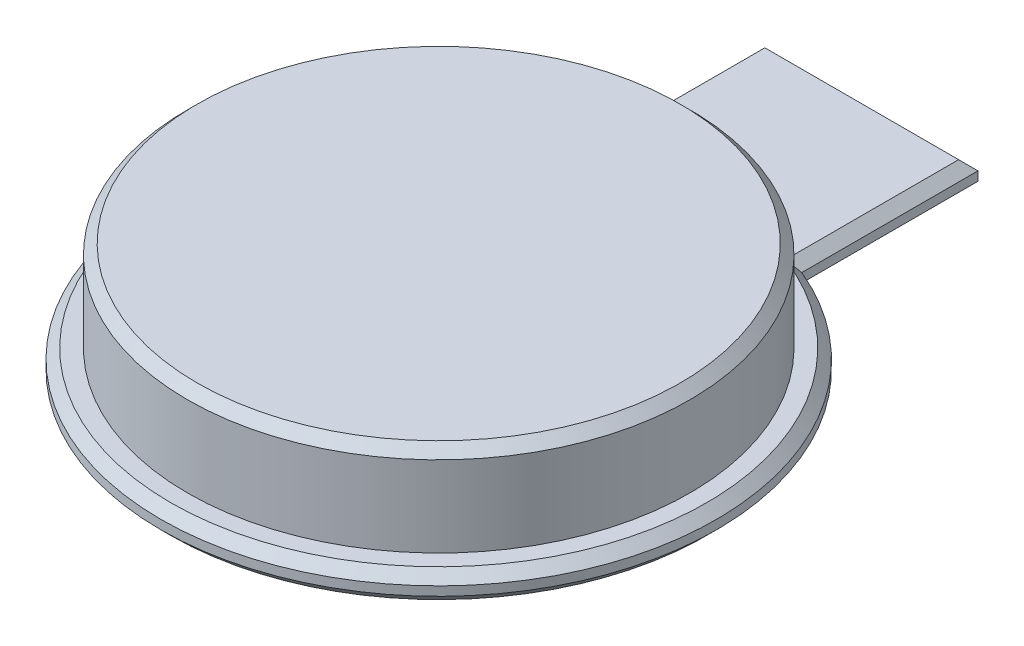
SolidWorks part; units mm, degrees
ref_plane "Front Plane" through (0, 0, 0) normal (0, 0, 1) x (1, 0, 0)
ref_plane "Top Plane" through (0, 0, 0) normal (0, 1, 0) x (1, 0, 0)
ref_plane "Right Plane" through (0, 0, 0) normal (1, 0, 0) x (0, 0, -1)
sketch "Sketch1" plane through (0, 0, 0) normal (0, 1, 0) x (1, 0, 0)
  line L0 (-8.25, 19.8542) -> (-8.25, 33.5)
  line L1 (-8.25, 33.5) -> (8.25, 33.5)
  line L2 (8.25, 33.5) -> (8.25, 19.8542)
  line L3 (0, 0) -> (0, 33.5) construction
  arc A0 (-8.25, 19.8542) -> (8.25, 19.8542) centre (0, 0) ccw
  point P1 (0, -21.5)
  dimension "D1" = 43
  dimension "D2" = 55
  dimension "D3" = 16.5
extrude "Boss-Extrude1" add sketch "Sketch1" along normal blind 2.2
sketch "Sketch2" plane through (0, 2.2, 0) normal (0, 1, 0) x (1, 0, 0)
  circle A0 centre (0, 0) radius 19.45
  dimension "D1" = 38.9
extrude "Boss-Extrude2" add sketch "Sketch2" along normal blind 7
chamfer "Chamfer1" distance 0.75 angle 45 9 edges at (8.25, 0, -26.6771) (0, 0, -33.5) (-8.25, 0, -26.6771) (0, 0, 21.5) (-8.25, 2.2, -26.6771) (0, 2.2, -33.5) (8.25, 2.2, -26.6771) (0, 2.2, 21.5) (0, 9.2, 19.45)
